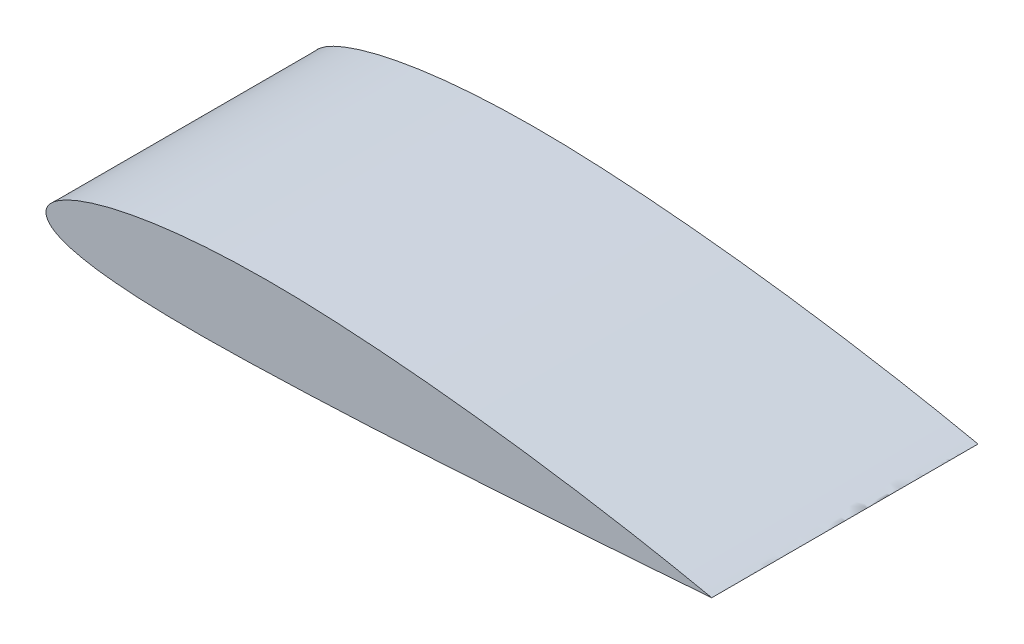
SolidWorks part; units mm, degrees
ref_plane "Front Plane" through (0, 0, 0) normal (0, 0, 1) x (1, 0, 0)
ref_plane "Top Plane" through (0, 0, 0) normal (0, 1, 0) x (1, 0, 0)
ref_plane "Right Plane" through (0, 0, 0) normal (1, 0, 0) x (0, 0, -1)
curve "Curve3"
  spline degree 3 poles (74.7505, -0.0114, 0) (75.062, -0.0041, 0) (74.7543, 0.0444, 0) (74.5025, 0.1111, 0) (73.8833, 0.2341, 0) (73.1152, 0.397, 0) (72.098, 0.6036, 0) (70.8804, 0.8474, 0) (69.4536, 1.125, 0) (67.8316, 1.4315, 0) (66.022, 1.7618, 0) (64.0362, 2.1106, 0) (61.8859, 2.4727, 0) (59.584, 2.8422, 0) (57.1444, 3.2139, 0) (54.5819, 3.5823, 0) (51.9122, 3.942, 0) (49.1513, 4.2878, 0) (46.3165, 4.6144, 0) (43.4252, 4.9167, 0) (40.4952, 5.1899, 0) (37.5448, 5.4291, 0) (34.5925, 5.6298, 0) (31.6535, 5.788, 0) (28.7417, 5.9014, 0) (25.8752, 5.9493, 0) (23.0762, 5.9316, 0) (20.3676, 5.8478, 0) (17.7672, 5.699, 0) (15.2922, 5.4875, 0) (12.9589, 5.217, 0) (10.7825, 4.8919, 0) (8.7769, 4.5183, 0) (6.9549, 4.1024, 0) (5.3274, 3.6515, 0) (3.9041, 3.1728, 0) (2.6926, 2.6737, 0) (1.6984, 2.161, 0) (0.924, 1.6397, 0) (0.3699, 1.111, 0) (0.0364, 0.5643, 0) (-0.0428, -0.0043, 0) (0.1472, -0.5454, 0) (0.5788, -1.0158, 0) (1.2193, -1.4278, 0) (2.0683, -1.7945, 0) (3.1245, -2.1181, 0) (4.3835, -2.3987, 0) (5.8383, -2.6357, 0) (7.4804, -2.8289, 0) (9.3, -2.9786, 0) (11.2862, -3.0859, 0) (13.4272, -3.1529, 0) (15.7108, -3.1818, 0) (18.1235, -3.1764, 0) (20.6518, -3.1404, 0) (23.2811, -3.0785, 0) (25.9966, -2.9957, 0) (28.7869, -2.8967, 0) (31.6395, -2.7878, 0) (34.5368, -2.6564, 0) (37.4569, -2.5081, 0) (40.379, -2.347, 0) (43.2852, -2.1767, 0) (46.1577, -2.0008, 0) (48.9791, -1.8224, 0) (51.7319, -1.6437, 0) (54.3991, -1.4675, 0) (56.9641, -1.295, 0) (59.4108, -1.1284, 0) (61.724, -0.9686, 0) (63.8891, -0.8173, 0) (65.8924, -0.6754, 0) (67.7212, -0.5441, 0) (69.3633, -0.4246, 0) (70.81, -0.3181, 0) (72.0464, -0.2252, 0) (73.0805, -0.1483, 0) (73.8626, -0.0855, 0) (74.4922, -0.0443, 0) (74.7505, -0.0114, 0) (75.062, -0.0041, 0) (74.7543, 0.0444, 0) knots -0.006851 -0.003054 -0.000765 0 0.000764 0.003054 0.006853 0.012137 0.018875 0.027023 0.036529 0.047336 0.059375 0.072571 0.086843 0.102101 0.118253 0.135196 0.152828 0.171038 0.189715 0.208741 0.228001 0.247374 0.26674 0.285981 0.305045 0.323835 0.342152 0.359885 0.376929 0.393182 0.408551 0.422947 0.436293 0.448516 0.459557 0.46937 0.477923 0.485208 0.491255 0.496154 0.500119 0.503573 0.507026 0.510984 0.51586 0.521855 0.529053 0.537476 0.547111 0.557924 0.569866 0.582879 0.596894 0.611837 0.627625 0.644171 0.661381 0.679159 0.697402 0.716092 0.735095 0.754231 0.773384 0.792437 0.811274 0.829776 0.847832 0.865327 0.882152 0.898204 0.913381 0.927587 0.940732 0.952732 0.963511 0.973 0.981136 0.987867 0.993149 0.996946 0.999235 1 1.000764 1.003054 1.006853 periodic
sketch "Sketch4" plane through (0, 0, 0) normal (0, 0, 1) x (1, 0, 0)
  spline S0 degree 3 poles (74.7505, -0.0114) (75.062, -0.0041) (74.7543, 0.0444) (74.5025, 0.1111) (73.8833, 0.2341) (73.1152, 0.397) (72.098, 0.6036) (70.8804, 0.8474) (69.4536, 1.125) (67.8316, 1.4315) (66.022, 1.7618) (64.0362, 2.1106) (61.8859, 2.4727) (59.584, 2.8422) (57.1444, 3.2139) (54.5819, 3.5823) (51.9122, 3.942) (49.1513, 4.2878) (46.3165, 4.6144) (43.4252, 4.9167) (40.4952, 5.1899) (37.5448, 5.4291) (34.5925, 5.6298) (31.6535, 5.788) (28.7417, 5.9014) (25.8752, 5.9493) (23.0762, 5.9316) (20.3676, 5.8478) (17.7672, 5.699) (15.2922, 5.4875) (12.9589, 5.217) (10.7825, 4.8919) (8.7769, 4.5183) (6.9549, 4.1024) (5.3274, 3.6515) (3.9041, 3.1728) (2.6926, 2.6737) (1.6984, 2.161) (0.924, 1.6397) (0.3699, 1.111) (0.0364, 0.5643) (-0.0428, -0.0043) (0.1472, -0.5454) (0.5788, -1.0158) (1.2193, -1.4278) (2.0683, -1.7945) (3.1245, -2.1181) (4.3835, -2.3987) (5.8383, -2.6357) (7.4804, -2.8289) (9.3, -2.9786) (11.2862, -3.0859) (13.4272, -3.1529) (15.7108, -3.1818) (18.1235, -3.1764) (20.6518, -3.1404) (23.2811, -3.0785) (25.9966, -2.9957) (28.7869, -2.8967) (31.6395, -2.7878) (34.5368, -2.6564) (37.4569, -2.5081) (40.379, -2.347) (43.2852, -2.1767) (46.1577, -2.0008) (48.9791, -1.8224) (51.7319, -1.6437) (54.3991, -1.4675) (56.9641, -1.295) (59.4108, -1.1284) (61.724, -0.9686) (63.8891, -0.8173) (65.8924, -0.6754) (67.7212, -0.5441) (69.3633, -0.4246) (70.81, -0.3181) (72.0464, -0.2252) (73.0805, -0.1483) (73.8626, -0.0855) (74.4922, -0.0443) (74.7505, -0.0114) (75.062, -0.0041) (74.7543, 0.0444) knots -0.006851 -0.003054 -0.000765 0 0.000764 0.003054 0.006853 0.012137 0.018875 0.027023 0.036529 0.047336 0.059375 0.072571 0.086843 0.102101 0.118253 0.135196 0.152828 0.171038 0.189715 0.208741 0.228001 0.247374 0.26674 0.285981 0.305045 0.323835 0.342152 0.359885 0.376929 0.393182 0.408551 0.422947 0.436293 0.448516 0.459557 0.46937 0.477923 0.485208 0.491255 0.496154 0.500119 0.503573 0.507026 0.510984 0.51586 0.521855 0.529053 0.537476 0.547111 0.557924 0.569866 0.582879 0.596894 0.611837 0.627625 0.644171 0.661381 0.679159 0.697402 0.716092 0.735095 0.754231 0.773384 0.792437 0.811274 0.829776 0.847832 0.865327 0.882152 0.898204 0.913381 0.927587 0.940732 0.952732 0.963511 0.973 0.981136 0.987867 0.993149 0.996946 0.999235 1 1.000764 1.003054 1.006853 only from (75, 0) to (75, 0) construction
  spline S1 degree 3 poles (74.7505, -0.0114) (75.062, -0.0041) (74.7543, 0.0444) (74.5025, 0.1111) (73.8833, 0.2341) (73.1152, 0.397) (72.098, 0.6036) (70.8804, 0.8474) (69.4536, 1.125) (67.8316, 1.4315) (66.022, 1.7618) (64.0362, 2.1106) (61.8859, 2.4727) (59.584, 2.8422) (57.1444, 3.2139) (54.5819, 3.5823) (51.9122, 3.942) (49.1513, 4.2878) (46.3165, 4.6144) (43.4252, 4.9167) (40.4952, 5.1899) (37.5448, 5.4291) (34.5925, 5.6298) (31.6535, 5.788) (28.7417, 5.9014) (25.8752, 5.9493) (23.0762, 5.9316) (20.3676, 5.8478) (17.7672, 5.699) (15.2922, 5.4875) (12.9589, 5.217) (10.7825, 4.8919) (8.7769, 4.5183) (6.9549, 4.1024) (5.3274, 3.6515) (3.9041, 3.1728) (2.6926, 2.6737) (1.6984, 2.161) (0.924, 1.6397) (0.3699, 1.111) (0.0364, 0.5643) (-0.0428, -0.0043) (0.1472, -0.5454) (0.5788, -1.0158) (1.2193, -1.4278) (2.0683, -1.7945) (3.1245, -2.1181) (4.3835, -2.3987) (5.8383, -2.6357) (7.4804, -2.8289) (9.3, -2.9786) (11.2862, -3.0859) (13.4272, -3.1529) (15.7108, -3.1818) (18.1235, -3.1764) (20.6518, -3.1404) (23.2811, -3.0785) (25.9966, -2.9957) (28.7869, -2.8967) (31.6395, -2.7878) (34.5368, -2.6564) (37.4569, -2.5081) (40.379, -2.347) (43.2852, -2.1767) (46.1577, -2.0008) (48.9791, -1.8224) (51.7319, -1.6437) (54.3991, -1.4675) (56.9641, -1.295) (59.4108, -1.1284) (61.724, -0.9686) (63.8891, -0.8173) (65.8924, -0.6754) (67.7212, -0.5441) (69.3633, -0.4246) (70.81, -0.3181) (72.0464, -0.2252) (73.0805, -0.1483) (73.8626, -0.0855) (74.4922, -0.0443) (74.7505, -0.0114) (75.062, -0.0041) (74.7543, 0.0444) knots -0.006851 -0.003054 -0.000765 0 0.000764 0.003054 0.006853 0.012137 0.018875 0.027023 0.036529 0.047336 0.059375 0.072571 0.086843 0.102101 0.118253 0.135196 0.152828 0.171038 0.189715 0.208741 0.228001 0.247374 0.26674 0.285981 0.305045 0.323835 0.342152 0.359885 0.376929 0.393182 0.408551 0.422947 0.436293 0.448516 0.459557 0.46937 0.477923 0.485208 0.491255 0.496154 0.500119 0.503573 0.507026 0.510984 0.51586 0.521855 0.529053 0.537476 0.547111 0.557924 0.569866 0.582879 0.596894 0.611837 0.627625 0.644171 0.661381 0.679159 0.697402 0.716092 0.735095 0.754231 0.773384 0.792437 0.811274 0.829776 0.847832 0.865327 0.882152 0.898204 0.913381 0.927587 0.940732 0.952732 0.963511 0.973 0.981136 0.987867 0.993149 0.996946 0.999235 1 1.000764 1.003054 1.006853 only from (75, 0) to (75, 0)
extrude "Boss-Extrude1" add sketch "Sketch4" along normal blind 30
